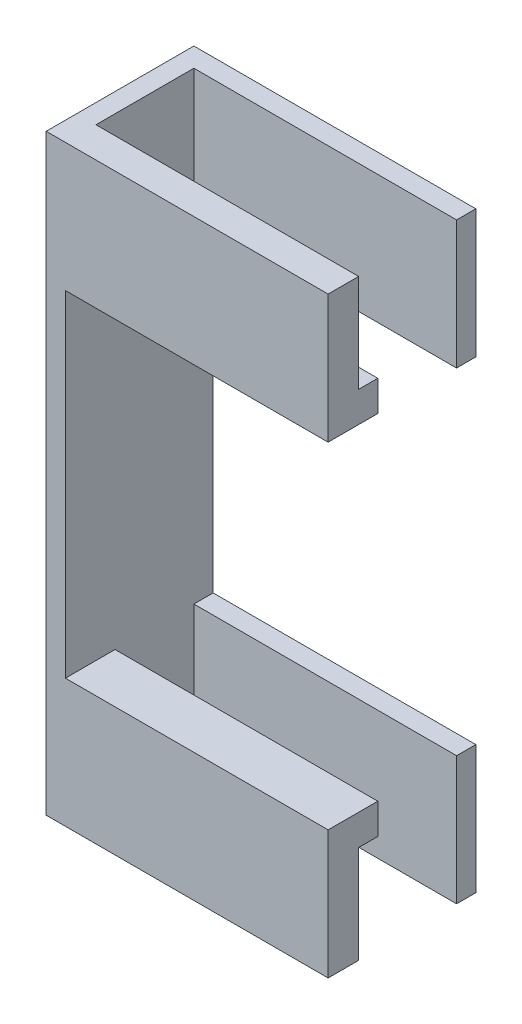
SolidWorks part; units mm, degrees
ref_plane "Front Plane" through (0, 0, 0) normal (0, 0, 1) x (1, 0, 0)
ref_plane "Top Plane" through (0, 0, 0) normal (0, 1, 0) x (1, 0, 0)
ref_plane "Right Plane" through (0, 0, 0) normal (1, 0, 0) x (0, 0, -1)
sketch "Sketch2" plane through (0, 0, 0) normal (1, 0, 0) x (0, 0, -1)
  line L0 (0, 0) -> (12.181, 0) construction
  line L1 (-8.001, 19.8501) -> (-8.001, 16.4973)
  line L2 (-8.001, 16.4973) -> (-6.4135, 16.4973)
  line L3 (-10.541, 19.8501) -> (-10.541, 13.9573)
  line L4 (-10.541, 13.9573) -> (-6.4135, 13.9573)
  line L5 (-10.541, 19.8501) -> (-8.001, 19.8501)
  line L6 (-6.4135, 16.4973) -> (-6.4135, 13.9573)
  line L7 (-6.4135, -16.4973) -> (-6.4135, -13.9573)
  line L8 (-10.541, -19.8501) -> (-8.001, -19.8501)
  line L9 (-10.541, -13.9573) -> (-6.4135, -13.9573)
  line L10 (-10.541, -19.8501) -> (-10.541, -13.9573)
  line L11 (-8.001, -16.4973) -> (-6.4135, -16.4973)
  line L12 (-8.001, -19.8501) -> (-8.001, -16.4973)
  dimension "D1" = 3.3528
  dimension "D2" = 1.5875
  dimension "D3" = 19.8501
  dimension "D4" = 8.001
  dimension "D5" = 2.54
extrude "Boss-Extrude2" add sketch "Sketch2" along normal blind 21.844
sketch "Sketch3" plane through (0, 0, 0) normal (-1, 0, 0) x (0, 0, 1)
  line L0 (6.4135, 16.4973) -> (6.4135, -16.4973) construction
  line L1 (10.541, 19.8501) -> (2.8641, 19.8501) construction
  line L3 (6.4135, 19.8501) -> (10.541, 19.8501)
  line L4 (6.4135, 19.8501) -> (6.4135, -19.8501)
  line L5 (6.4135, -19.8501) -> (10.541, -19.8501)
  line L6 (10.541, 19.8501) -> (10.541, -19.8501)
  point P13 (10.541, -19.8501)
extrude "Boss-Extrude3" add sketch "Sketch3" along normal blind 1.6002
sketch "Sketch4" plane through (0, 0, 6.4135) normal (0, 0, -1) x (-1, 0, 0)
  line L1 (0, 19.8501) -> (1.6002, 19.8501)
  line L2 (0, 19.8501) -> (0, -19.8501)
  line L3 (0, -19.8501) -> (1.6002, -19.8501)
  line L4 (1.6002, 19.8501) -> (1.6002, -19.8501)
extrude "Boss-Extrude4" add sketch "Sketch4" along normal blind 6.5532
sketch "Sketch5" plane through (0, 0, -0.1397) normal (0, 0, -1) x (-1, 0, 0)
  line L1 (-21.844, 19.8501) -> (1.6002, 19.8501)
  line L2 (-21.844, 19.8501) -> (-21.844, -19.8501)
  line L3 (-21.844, -19.8501) -> (1.6002, -19.8501)
  line L4 (1.6002, 19.8501) -> (1.6002, -19.8501)
extrude "Boss-Extrude5" add sketch "Sketch5" along normal blind 1.6002
sketch "Sketch6" plane through (0, 19.8501, 0) normal (0, 1, 0) x (1, 0, 0)
  line L8 (21.844, -8.001) -> (0, -8.001)
  line L9 (0, -8.001) -> (0, 0.1397)
  line L10 (0, 0.1397) -> (21.844, 0.1397)
  line L11 (21.844, 0.1397) -> (21.844, 1.7399)
  line L12 (21.844, 1.7399) -> (-1.6002, 1.7399)
  line L13 (-1.6002, 1.7399) -> (-1.6002, -10.541)
  line L14 (-1.6002, -10.541) -> (21.844, -10.541)
  line L15 (21.844, -10.541) -> (21.844, -8.001)
  line L16 (21.844, -8.001) -> (0, -8.001)
  line L17 (0, -8.001) -> (0, 0.1397)
  line L18 (0, 0.1397) -> (21.844, 0.1397)
  line L19 (21.844, 0.1397) -> (21.844, 1.7399)
  line L20 (21.844, 1.7399) -> (-1.6002, 1.7399)
  line L21 (-1.6002, 1.7399) -> (-1.6002, -10.541)
  line L22 (-1.6002, -10.541) -> (21.844, -10.541)
  line L23 (21.844, -10.541) -> (21.844, -8.001)
  dimension "D1" = 0
extrude "Boss-Extrude6" add sketch "Sketch6" along normal blind 4.7752
mirror "Mirror1" about plane through (0, 0, 0) normal (0, 1, 0) of "Boss-Extrude6"
sketch "Sketch7" plane through (0, 0, -0.1397) normal (0, 0, 1) x (1, 0, 0)
  line L1 (21.844, -13.9573) -> (0, -13.9573)
  line L2 (21.844, -13.9573) -> (21.844, 13.9573)
  line L3 (21.844, 13.9573) -> (0, 13.9573)
  line L4 (0, -13.9573) -> (0, 13.9573)
extrude "Cut-Extrude1" cut sketch "Sketch7" against normal blind 6.35
